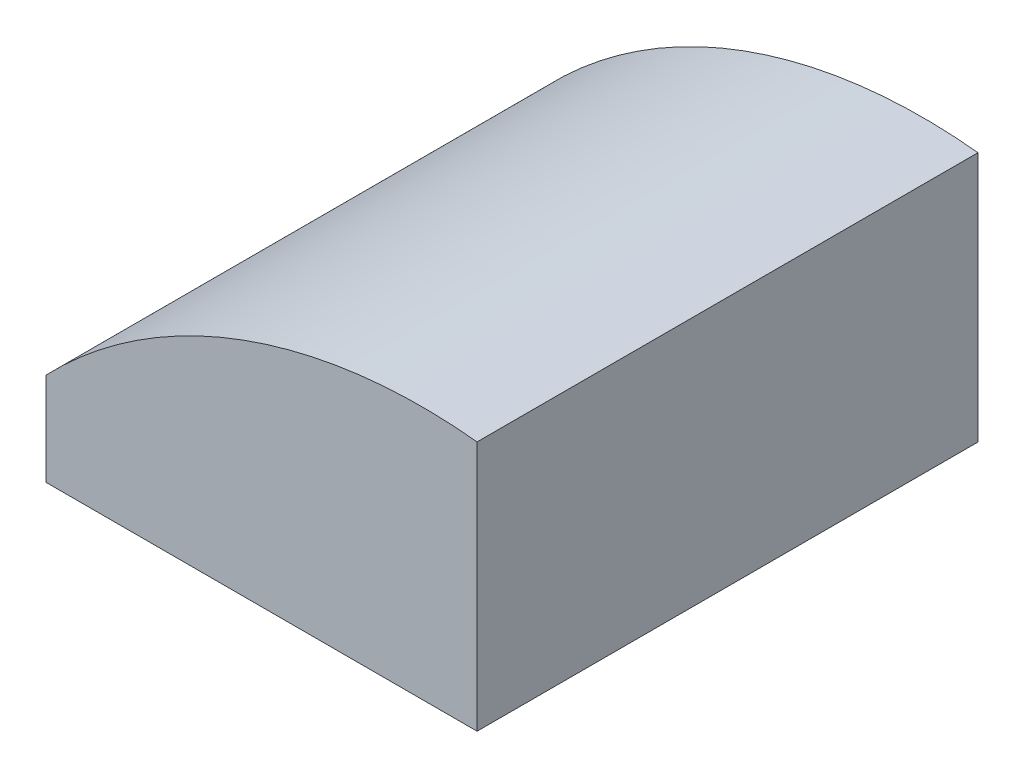
SolidWorks part; units mm, degrees
ref_plane "Front Plane" through (0, 0, 0) normal (0, 0, 1) x (1, 0, 0)
ref_plane "Top Plane" through (0, 0, 0) normal (0, 1, 0) x (1, 0, 0)
ref_plane "Right Plane" through (0, 0, 0) normal (1, 0, 0) x (0, 0, -1)
sketch "Sketch1" plane through (0, 0, 0) normal (0, 0, 1) x (1, 0, 0)
  line L0 (0, 0) -> (0, 9.4202)
  line L1 (43.7182, 25.4137) -> (43.7182, 0)
  line L3 (43.7182, 0) -> (0, 0)
  arc A0 (0, 9.4202) -> (43.7182, 25.4137) centre (38.1425, -27.0936) cw
extrude "Extrude1" add sketch "Sketch1" against normal blind 50.8
ref_plane "Plane1" through (20.0015, 22.4948, 0) normal (-0.3436, 0.9391, 0) x (0.9391, 0.3436, 0)
